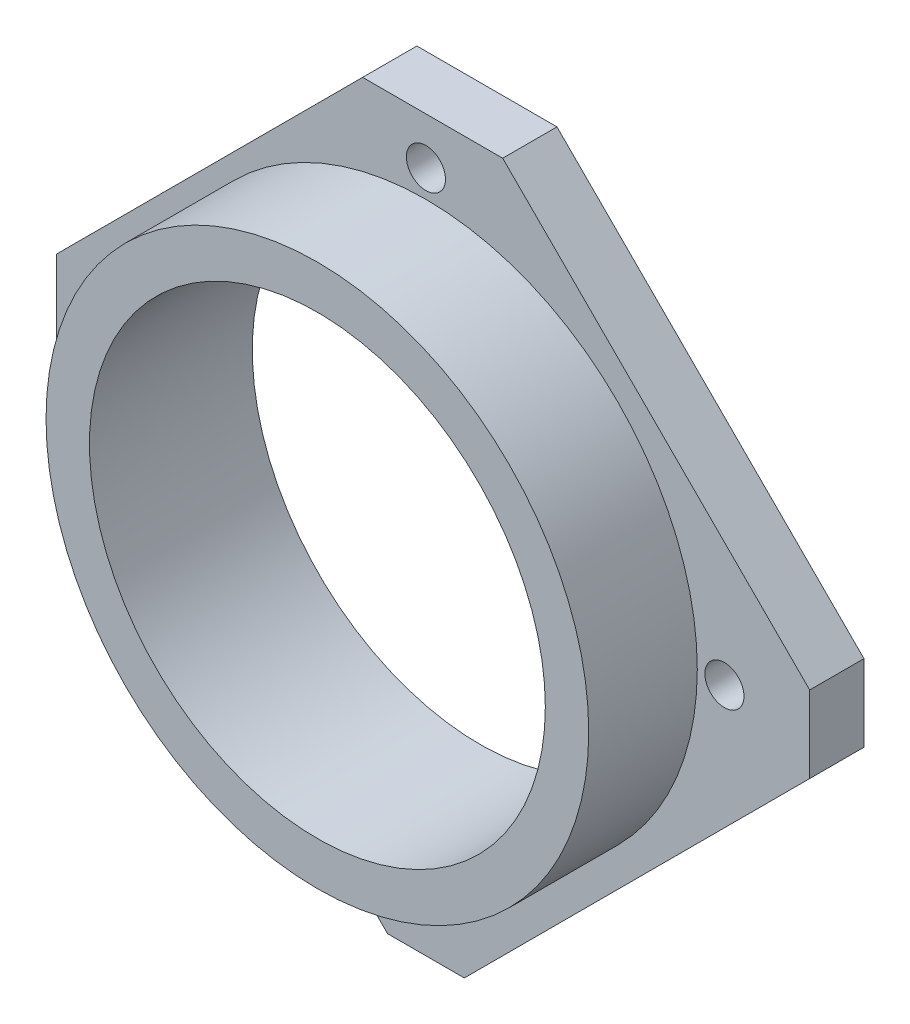
SolidWorks part; units mm, degrees
ref_plane "前视基准面" through (0, 0, 0) normal (0, 0, 1) x (1, 0, 0)
ref_plane "上视基准面" through (0, 0, 0) normal (0, 1, 0) x (1, 0, 0)
ref_plane "右视基准面" through (0, 0, 0) normal (1, 0, 0) x (0, 0, -1)
sketch "Sketch1" plane through (0, 0, 0) normal (0, 0, 1) x (1, 0, 0)
  line L0 (-3.5355, -35.3553) -> (-22.9362, -15.9547) construction
  line L1 (3.5355, -35.3553) -> (-3.5355, -35.3553) construction
  line L2 (35.3553, -3.5355) -> (3.5355, -35.3553) construction
  line L3 (35.3553, 3.5355) -> (35.3553, -3.5355) construction
  line L4 (7.0711, 31.8198) -> (35.3553, 3.5355) construction
  line L5 (7.0711, 31.8198) -> (-5.8328, 31.8198) construction
  line L6 (-3.5355, -35.3553) -> (-34.0291, -4.8618)
  line L7 (3.5355, -35.3553) -> (-3.5355, -35.3553)
  line L8 (35.3553, -3.5355) -> (3.5355, -35.3553)
  line L9 (35.3553, 3.5355) -> (35.3553, -3.5355)
  line L10 (7.0711, 31.8198) -> (35.3553, 3.5355)
  line L11 (7.0711, 31.8198) -> (-5.8328, 31.8198)
  line L12 (-34.0291, 3.6235) -> (-5.8328, 31.8198)
  line L13 (-34.0291, -4.8618) -> (-34.0291, 3.6235)
  line L14 (0, 27.5) -> (27.5, 0) construction
  line L15 (0, 27.5) -> (-27.5, 0) construction
  line L16 (27.5, 0) -> (0, -27.5) construction
  line L17 (-27.5, 0) -> (0, -27.5) construction
  circle A4 centre (27.5, 0) radius 1.8
  circle A5 centre (0, -27.5) radius 1.8
  circle A7 centre (0, 27.5) radius 1.8
  circle A9 centre (0, 0) radius 21
  circle A10 centre (-27.5, 0) radius 1.8
  point P1 (-38.2717, -0.6191)
  dimension "D1" = 42
  dimension "D2" = 3.6
  dimension "D3" = 3.6
  dimension "D5" = 3.6
  dimension "D6" = 3.6
extrude "Boss-Extrude1" add sketch "Sketch1" along normal blind 5
sketch "Sketch2" plane through (0, 0, 5) normal (0, 0, 1) x (1, 0, 0)
  circle A0 centre (0, 0) radius 21
  circle A1 centre (0, 0) radius 25
  dimension "D1" = 50
extrude "Boss-Extrude2" add sketch "Sketch2" along normal blind 10
